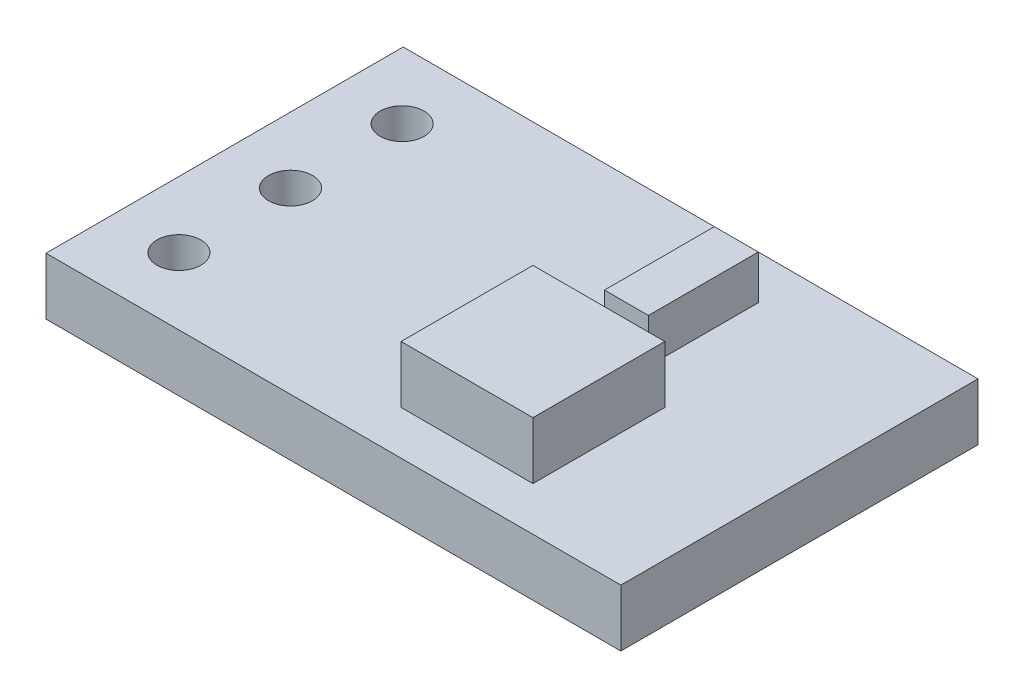
SolidWorks part; units mm, degrees
ref_plane "Front Plane" through (0, 0, 0) normal (0, 0, 1) x (1, 0, 0)
ref_plane "Top Plane" through (0, 0, 0) normal (0, 1, 0) x (1, 0, 0)
ref_plane "Right Plane" through (0, 0, 0) normal (1, 0, 0) x (0, 0, -1)
sketch "Sketch1" plane through (0, 0, 0) normal (0, 1, 0) x (1, 0, 0)
  line L0 (-5.0405, 0) -> (0, 0) construction
  line L1 (6.5405, -4.064) -> (-6.5405, -4.064)
  line L2 (6.5405, -4.064) -> (6.5405, 4.064)
  line L3 (6.5405, 4.064) -> (-6.5405, 4.064)
  line L4 (-6.5405, -4.064) -> (-6.5405, 4.064)
  line L5 (6.5405, -4.064) -> (-6.5405, 4.064) construction
  line L6 (6.5405, 4.064) -> (-6.5405, -4.064) construction
  line L7 (-5.0405, -2.54) -> (-5.0405, 2.54) construction
  circle A0 centre (-5.0405, 2.54) radius 0.5
  circle A1 centre (-5.0405, 0) radius 0.5
  circle A2 centre (-5.0405, -2.54) radius 0.5
  point P0 (0, 0)
  dimension "D5" = 1
  dimension "D6" = 1
  dimension "D7" = 1
  dimension "D1" = 8.128
  dimension "D2" = 13.081
  dimension "D3" = 2.54
  dimension "D4" = 2.54
  dimension "D8" = 1.5
extrude "Boss-Extrude1" add sketch "Sketch1" along normal blind 1.3
sketch "Sketch2" plane through (0, 1.3, 0) normal (0, 1, 0) x (1, 0, 0)
  line L0 (-6.5405, -4.064) -> (6.5405, -4.064) construction
  line L1 (3.5405, -0.064) -> (0.5405, -0.064)
  line L2 (3.5405, -0.064) -> (3.5405, -3.064)
  line L3 (3.5405, -3.064) -> (0.5405, -3.064)
  line L4 (0.5405, -0.064) -> (0.5405, -3.064)
  line L5 (3.5405, -0.064) -> (0.5405, -3.064) construction
  line L6 (3.5405, -3.064) -> (0.5405, -0.064) construction
  line L7 (6.5405, -4.064) -> (6.5405, 4.064) construction
  point P0 (2.0405, -1.564)
  dimension "D1" = 1
  dimension "D2" = 3
  dimension "D3" = 3
  dimension "D4" = 3
extrude "Boss-Extrude2" add sketch "Sketch2" along normal blind 1.3
sketch "Sketch3" plane through (0, 1.3, 0) normal (0, 1, 0) x (1, 0, 0)
  line L0 (6.5405, 4.064) -> (-6.5405, 4.064) construction
  line L1 (2.5405, 3.064) -> (1.5405, 3.064)
  line L2 (2.5405, 3.064) -> (2.5405, 0.564)
  line L3 (2.5405, 0.564) -> (1.5405, 0.564)
  line L4 (1.5405, 3.064) -> (1.5405, 0.564)
  line L5 (2.5405, 3.064) -> (1.5405, 0.564) construction
  line L6 (2.5405, 0.564) -> (1.5405, 3.064) construction
  line L7 (6.5405, -4.064) -> (6.5405, 4.064) construction
  point P0 (2.0405, 1.814)
  dimension "D1" = 1
  dimension "D2" = 4
  dimension "D3" = 1
  dimension "D4" = 2.5
extrude "Boss-Extrude3" add sketch "Sketch3" along normal blind 1
